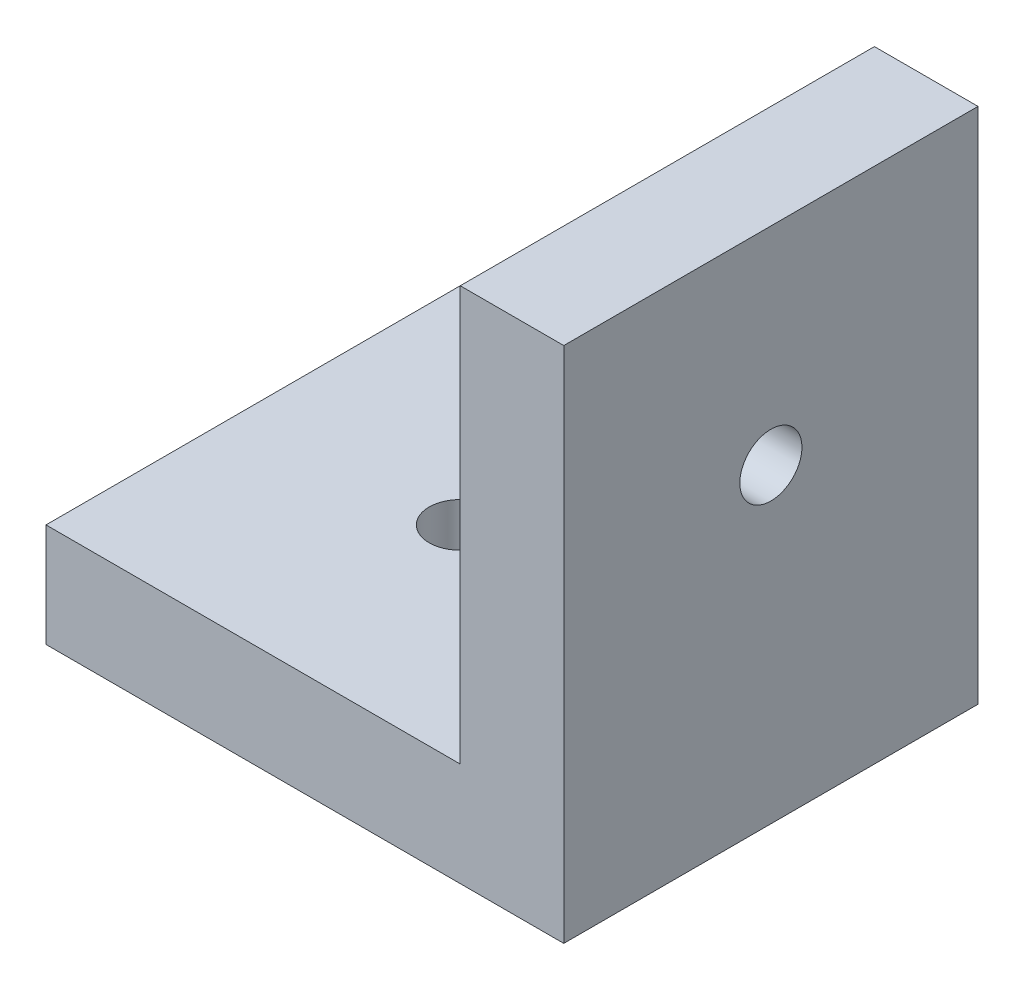
SolidWorks part; units mm, degrees
ref_plane "前视基准面" through (0, 0, 0) normal (0, 0, 1) x (1, 0, 0)
ref_plane "上视基准面" through (0, 0, 0) normal (0, 1, 0) x (1, 0, 0)
ref_plane "右视基准面" through (0, 0, 0) normal (1, 0, 0) x (0, 0, -1)
sketch "草图1" plane through (0, 0, 0) normal (0, 0, 1) x (1, 0, 0)
  line L1 (0, 0) -> (5, 0)
  line L2 (0, 0) -> (0, -25)
  line L3 (0, -25) -> (5, -25)
  line L4 (5, 0) -> (5, -25)
  line L5 (5, -25) -> (-20, -25)
  line L6 (5, -25) -> (5, -20)
  line L7 (5, -20) -> (-20, -20)
  line L8 (-20, -25) -> (-20, -20)
  dimension "D1" = 5
  dimension "D2" = 25
  dimension "D3" = 5
  dimension "D4" = 25
extrude "凸台-拉伸1" add sketch "草图1" along normal blind 20 contours L7 L4 L1 L2 | L4 L7 L2 L3 | L8 L5 L2 L7
sketch "草图2" plane through (0, -20, 0) normal (0, 1, 0) x (1, 0, 0)
  line L1 (-10, 0) -> (-10, -20) construction
  line L2 (0, 0) -> (-20, 0) construction
  line L3 (0, -20) -> (-20, -20) construction
  circle A0 centre (-10, -10) radius 1.5
  dimension "D1" = 3
extrude "切除-拉伸1" cut sketch "草图2" against normal up to next
sketch "草图3" plane through (0, 0, 0) normal (-1, 0, 0) x (0, 0, 1)
  line L0 (10, 0) -> (10, -20) construction
  line L1 (20, 0) -> (0, 0) construction
  line L2 (20, -20) -> (0, -20) construction
  circle A0 centre (10, -10) radius 1.5
  dimension "D1" = 3
extrude "切除-拉伸2" cut sketch "草图3" against normal up to next
